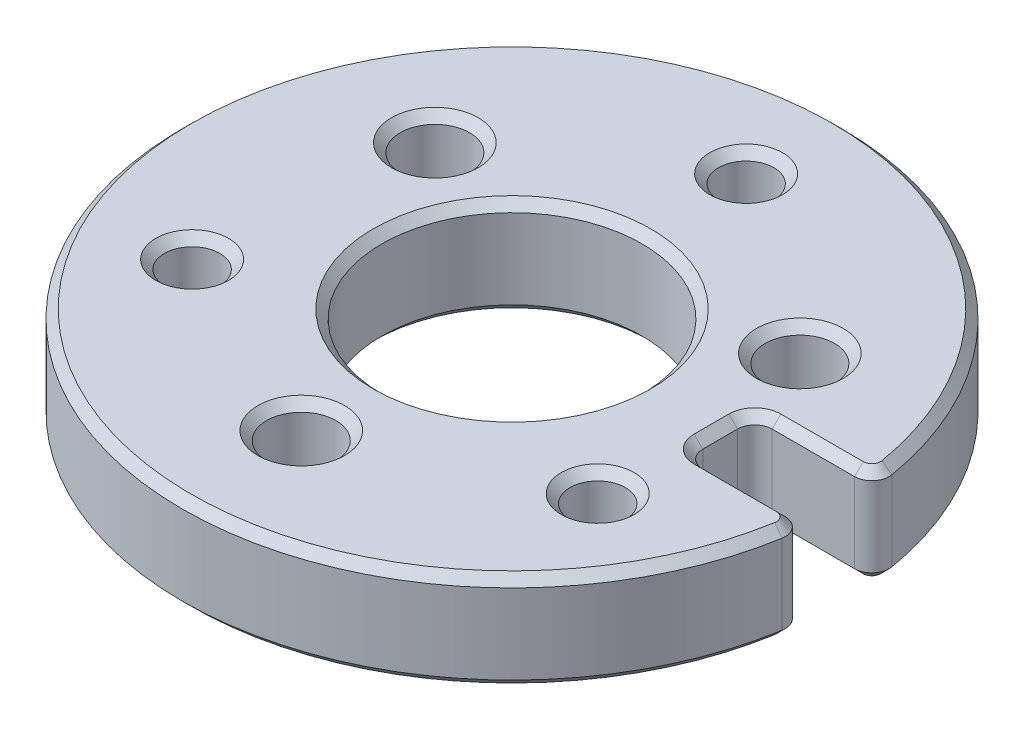
SolidWorks part; units mm, degrees
material "6061 合金"
ref_plane "Front Plane" through (0, 0, 0) normal (0, 0, 1) x (1, 0, 0)
ref_plane "Top Plane" through (0, 0, 0) normal (0, 1, 0) x (1, 0, 0)
ref_plane "Right Plane" through (0, 0, 0) normal (1, 0, 0) x (0, 0, -1)
other "Configuration Table"
sketch "草图1" plane through (0, 0, 0) normal (0, 1, 0) x (1, 0, 0)
  line L0 (0, 0) -> (-10.5222, 6.075) construction
  line L1 (0, 0) -> (-19, 0) construction
  circle A0 centre (0, 0) radius 19
  circle A1 centre (0, 0) radius 13.5 construction
  circle A2 centre (0, 13.5) radius 1.6
  circle A3 centre (11.6913, -6.75) radius 1.6
  circle A4 centre (-11.6913, -6.75) radius 1.6
  circle A5 centre (0, 0) radius 7.5
  circle A6 centre (-10.5222, 6.075) radius 2
  circle A7 centre (0, 0) radius 7.5
  circle A8 centre (10.5222, 6.075) radius 2
  circle A9 centre (0, 0) radius 7.5
  circle A10 centre (0, -12.15) radius 2
  circle A11 centre (0, 0) radius 12.15 construction
  point P22 (0, 0)
  dimension "D1" = 38
  dimension "D2" = 27
  dimension "D3" = 3.2
  dimension "D4" = 15
  dimension "D5" = 4
  dimension "D8" = 24.3
  dimension "D6" = 30
  dimension "D9" = 3
  dimension "D7" = 3
extrude "凸台-拉伸1" add sketch "草图1" along normal blind 5.6 contours A0 A10 A8 A6 A5 A4 A3 A2
sketch "草图2" plane through (0, 5.6, 0) normal (0, 1, 0) x (1, 0, 0)
  line L0 (0, 0) -> (19, 0) construction
  line L2 (12, 2) -> (27.1782, 2)
  line L3 (12, 2) -> (12, -2)
  line L4 (12, -2) -> (27.1782, -2)
  line L5 (27.1782, 2) -> (27.1782, -2)
  circle A0 centre (0, 0) radius 19 construction
  dimension "D1" = 7
  dimension "D2" = 2
extrude "切除-拉伸1" cut sketch "草图2" against normal blind 10
fillet "圆角1" radius 1 4 edges at (18.8944, 2.8, 2) (18.8944, 2.8, -2) (12, 2.8, 2) (12, 2.8, -2)
sketch "草图3" plane through (0, 5.6, 0) normal (0, 1, 0) x (1, 0, 0)
  line L3 (17.7482, -2) -> (13, -2)
  line L4 (12, -1) -> (12, 1)
  line L5 (13, 2) -> (17.7482, 2)
  line L6 (17.7482, -2) -> (13, -2)
  line L7 (12, -1) -> (12, 1)
  line L8 (13, 2) -> (17.7482, 2)
  circle A0 centre (11.6913, -6.75) radius 1.6 construction
  circle A1 centre (-11.6913, -6.75) radius 1.6 construction
  circle A2 centre (0, 13.5) radius 1.6 construction
  circle A3 centre (0, 0) radius 7.5 construction
  circle A4 centre (11.6913, -6.75) radius 1.6
  arc A5 (18.7343, 3.1667) -> (18.7343, -3.1667) centre (0, 0) ccw
  arc A6 (18.7343, -3.1667) -> (17.7482, -2) centre (17.7482, -3) ccw
  arc A7 (12, -1) -> (13, -2) centre (13, -1) ccw
  arc A8 (13, 2) -> (12, 1) centre (13, 1) ccw
  arc A9 (17.7482, 2) -> (18.7343, 3.1667) centre (17.7482, 3) ccw
  arc A10 (18.7343, 3.1667) -> (18.7343, -3.1667) centre (0, 0) ccw
  arc A11 (18.7343, -3.1667) -> (17.7482, -2) centre (17.7482, -3) ccw
  arc A12 (12, -1) -> (13, -2) centre (13, -1) ccw
  arc A13 (13, 2) -> (12, 1) centre (13, 1) ccw
  arc A14 (17.7482, 2) -> (18.7343, 3.1667) centre (17.7482, 3) ccw
  circle A15 centre (-11.6913, -6.75) radius 1.6
  circle A16 centre (0, 13.5) radius 1.6
  circle A17 centre (0, 0) radius 7.5
  dimension "D1" = 0
chamfer "倒角1" distance 0.5 angle 45 16 edges at (12, 0, 0) (12.2929, 0, -1.7071) (12.2929, 0, 1.7071) (15.3741, 0, -2) (15.3741, 0, 2) (18.512, 0, -2.3545) (18.512, 0, 2.3545) (-19, 0, 0) (12, 5.6, 0) (12.2929, 5.6, -1.7071) (12.2929, 5.6, 1.7071) (15.3741, 5.6, -2) (15.3741, 5.6, 2) (18.512, 5.6, -2.3545) (18.512, 5.6, 2.3545) (-19, 5.6, 0)
chamfer "倒角2" distance 0.5 angle 45 14 edges at (10.5222, 5.6, -4.075) (11.6913, 5.6, 8.35) (0, 5.6, 14.15) (-11.6913, 5.6, 8.35) (-10.5222, 5.6, -4.075) (0, 5.6, -11.9) (10.5222, 0, -4.075) (11.6913, 0, 8.35) (0, 0, 14.15) (-11.6913, 0, 8.35) (-10.5222, 0, -4.075) (0, 0, -11.9) (0, 0, 7.5) (0, 5.6, 7.5)
